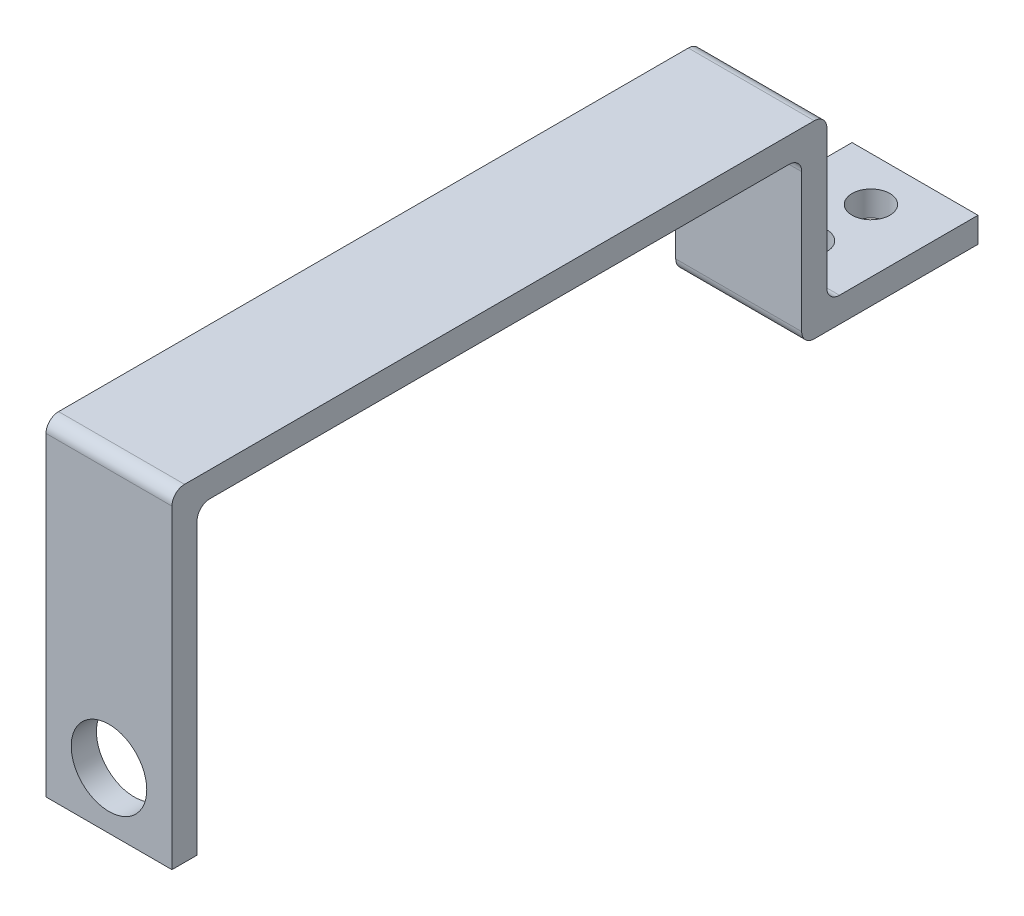
SolidWorks part; units mm, degrees
ref_plane "Front Plane" through (0, 0, 0) normal (0, 0, 1) x (1, 0, 0)
ref_plane "Top Plane" through (0, 0, 0) normal (0, 1, 0) x (1, 0, 0)
ref_plane "Right Plane" through (0, 0, 0) normal (1, 0, 0) x (0, 0, -1)
sketch "Sketch1" plane through (0, 0, 0) normal (0, 1, 0) x (1, 0, 0)
  line L1 (-5.087, 7.0435) -> (4.913, 7.0435)
  line L2 (-5.087, 7.0435) -> (-5.087, -4.9565)
  line L3 (-5.087, -4.9565) -> (4.913, -4.9565)
  line L4 (4.913, 7.0435) -> (4.913, -4.9565)
  circle A0 centre (-0.087, -1.4565) radius 1.5
  circle A1 centre (-0.087, 3.5435) radius 1.5
  dimension "D2" = 3
  dimension "D3" = 3
  dimension "D4" = 5
  dimension "D5" = 3.5
  dimension "D6" = 3.5
  dimension "D1" = 10
extrude "Boss-Extrude1" add sketch "Sketch1" along normal blind 2
sketch "Sketch2" plane through (0, 0, 4.9565) normal (0, 0, 1) x (1, 0, 0)
  line L0 (4.913, 2) -> (4.913, 0) construction
  line L1 (-5.087, 0) -> (4.913, 0)
  line L2 (-5.087, 0) -> (-5.087, 13)
  line L3 (-5.087, 13) -> (4.913, 13)
  line L4 (4.913, 0) -> (4.913, 13)
  dimension "D1" = 0
  dimension "D2" = 13
extrude "Boss-Extrude2" add sketch "Sketch2" along normal blind 2
sketch "Sketch3" plane through (0, 13, 0) normal (0, 1, 0) x (1, 0, 0)
  line L0 (4.913, -6.9565) -> (4.913, -4.9565) construction
  line L1 (-5.087, -4.9565) -> (4.913, -4.9565)
  line L2 (-5.087, -4.9565) -> (-5.087, -54.9565)
  line L3 (-5.087, -54.9565) -> (4.913, -54.9565)
  line L4 (4.913, -4.9565) -> (4.913, -54.9565)
  dimension "D1" = 0
  dimension "D2" = 50
extrude "Boss-Extrude3" add sketch "Sketch3" along normal blind 2
sketch "Sketch4" plane through (0, 0, 54.9565) normal (0, 0, 1) x (1, 0, 0)
  line L0 (4.913, 15) -> (4.913, 13) construction
  line L1 (-5.087, 15) -> (4.913, 15)
  line L2 (-5.087, 15) -> (-5.087, -11)
  line L3 (-5.087, -11) -> (4.913, -11)
  line L4 (4.913, 15) -> (4.913, -11)
  line L5 (4.913, 13) -> (-5.087, 13) construction
  circle A0 centre (-0.087, -6.5) radius 3
  dimension "D3" = 6
  dimension "D4" = 19.5
  dimension "D1" = 0
  dimension "D2" = 26
extrude "Boss-Extrude4" add sketch "Sketch4" along normal blind 2
fillet "Fillet1" radius 1 1 edges at (-0.087, 15, 56.9565)
fillet "Fillet2" radius 1 1 edges
fillet "Fillet3" radius 1 1 edges at (-0.087, 15, 4.9565)
fillet "Fillet4" radius 1 1 edges
fillet "Fillet5" radius 1 1 edges at (-0.087, 0, 6.9565)
fillet "Fillet6" radius 1 1 edges
